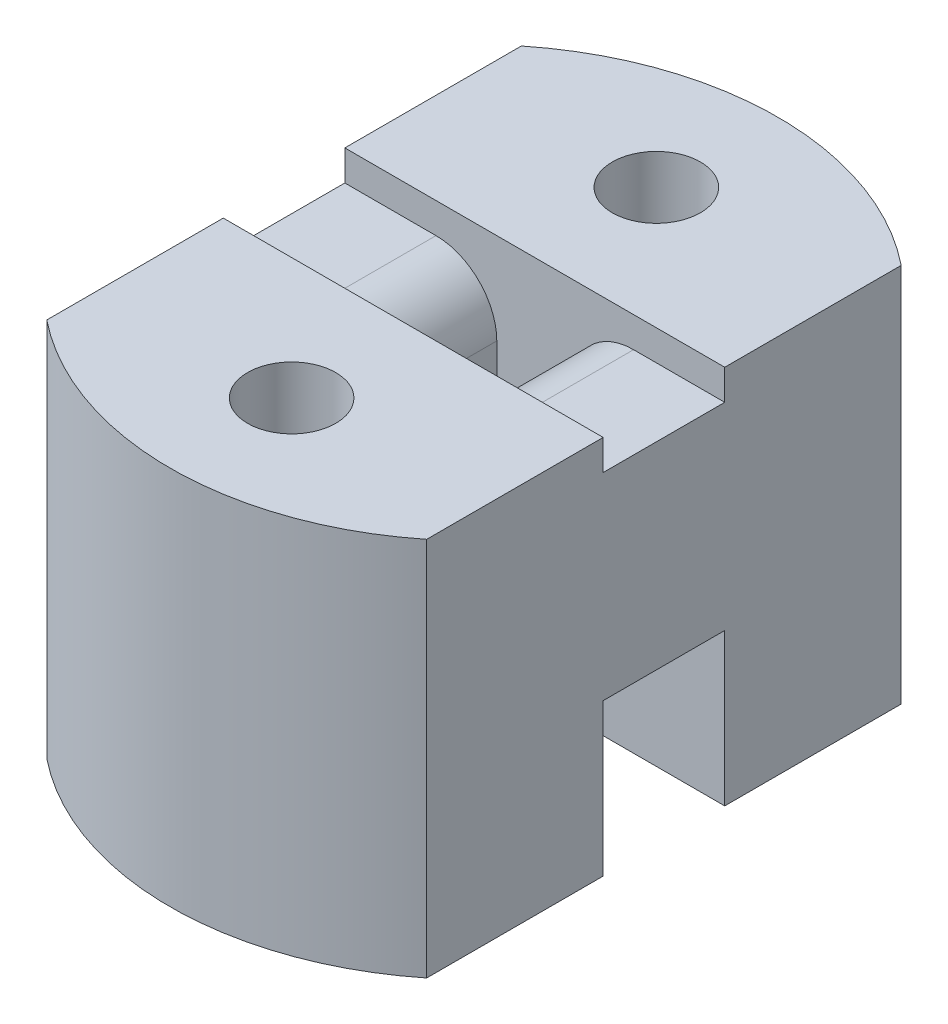
SolidWorks part; units mm, degrees
ref_plane "Front Plane" through (0, 0, 0) normal (0, 0, 1) x (1, 0, 0)
ref_plane "Top Plane" through (0, 0, 0) normal (0, 1, 0) x (1, 0, 0)
ref_plane "Right Plane" through (0, 0, 0) normal (1, 0, 0) x (0, 0, -1)
sketch "Sketch1" plane through (0, 0, 0) normal (0, 1, 0) x (1, 0, 0)
  circle A0 centre (0, 0) radius 20
  dimension "D1" = 40
extrude "Boss-Extrude1" add sketch "Sketch1" along normal blind 25
sketch "Sketch2" plane through (0, 25, 0) normal (0, 1, 0) x (1, 0, 0)
  line L0 (20, 0) -> (0, 0) construction
  line L1 (-20, 4) -> (20, 4)
  line L2 (-20, 4) -> (-20, -4)
  line L3 (-20, -4) -> (20, -4)
  line L4 (20, 4) -> (20, -4)
  circle A0 centre (0, 0) radius 20 construction
  dimension "D1" = 8
extrude "Cut-Extrude1" cut sketch "Sketch2" against normal blind 2
sketch "Sketch3" plane through (0, 25, 0) normal (0, 1, 0) x (1, 0, 0)
  line L0 (0, 0) -> (0, 12) construction
  line L3 (0, 0) -> (0, -12) construction
  dimension "D1" = 12
hole_wizard "M5 Clearance Hole1" positions "3DSketch1" profile "Sketch4" hole size "M5" standard "ANSI Metric" end condition through all
sketch3d "3DSketch1"
  point P0 (0, 25, -12)
  point P3 (0, 25, 12)
sketch "Sketch4" plane through (0, 25, -12) normal (1, 0, 0) x (0, 0, 1)
  line L0 (0, 0) -> (0, 25)
  line L1 (0, 25) -> (2.9, 25)
  line L2 (2.9, 25) -> (2.9, 0)
  line L5 (2.9, 0) -> (0, 0)
  line L11 (0, -6.35) -> (0, 107.95) construction
  dimension "Thru Hole Dia." = 5.8
  dimension "Thru Hole Depth" = 25
sketch "Sketch5" plane through (0, 0, 0) normal (0, -1, 0) x (1, 0, 0)
  line L1 (4.9075, 12) -> (2.4537, 16.25)
  line L2 (2.4537, 16.25) -> (-2.4537, 16.25)
  line L3 (-2.4537, 16.25) -> (-4.9075, 12)
  line L4 (-4.9075, 12) -> (-2.4537, 7.75)
  line L5 (-2.4537, 7.75) -> (2.4537, 7.75)
  line L6 (2.4537, 7.75) -> (4.9075, 12)
  line L7 (4.9075, -12) -> (2.4537, -7.75)
  line L8 (2.4537, -7.75) -> (-2.4537, -7.75)
  line L9 (-2.4537, -7.75) -> (-4.9075, -12)
  line L10 (-4.9075, -12) -> (-2.4537, -16.25)
  line L11 (-2.4537, -16.25) -> (2.4537, -16.25)
  line L12 (2.4537, -16.25) -> (4.9075, -12)
  circle A0 centre (0, 12) radius 4.25 construction
  circle A1 centre (0, -12) radius 4.25 construction
  dimension "D1" = 8.5
extrude "Cut-Extrude2" cut sketch "Sketch5" against normal blind 6 contours L5 L6 L1 L2 L3 L4
sketch "Sketch6" plane through (0, 23, 0) normal (0, 1, 0) x (1, 0, 0)
  line L0 (19.5959, 4) -> (-19.5959, 4) construction
  line L1 (-2.5, 4) -> (2.5, 4)
  line L2 (-2.5, 4) -> (-2.5, -4)
  line L3 (-2.5, -4) -> (2.5, -4)
  line L4 (2.5, 4) -> (2.5, -4)
  line L5 (-19.5959, -4) -> (19.5959, -4) construction
  point P8 (0, 4)
  dimension "D1" = 5
extrude "Cut-Extrude3" cut sketch "Sketch6" against normal through all both and the other way through all
sketch "Sketch7" plane through (0, 0, 0) normal (0, -1, 0) x (1, 0, 0)
  line L0 (-20, -4) -> (-20, 4) construction
  line L1 (20, -4) -> (20, 4) construction
  line L2 (-20, -4) -> (20, -4) construction
  line L3 (-20, 4) -> (20, 4) construction
  line L4 (-20, -4) -> (-20, 4)
  line L5 (20, -4) -> (20, 4)
  line L6 (-20, -4) -> (20, -4)
  line L7 (-20, 4) -> (20, 4)
extrude "Cut-Extrude4" cut sketch "Sketch7" against normal blind 10
fillet "Fillet1" radius 4 4 edges at (-2.5, 23, 0) (2.5, 23, 0) (-2.5, 10, 0) (2.5, 10, 0)
sketch "Sketch8" plane through (0, 25, 0) normal (0, 1, 0) x (1, 0, 0)
  line L0 (0, 0) -> (0, 20) construction
  line L1 (-12.5, 20) -> (12.5, 20)
  line L2 (-12.5, 20) -> (-12.5, -20)
  line L3 (-12.5, -20) -> (12.5, -20)
  line L4 (12.5, 20) -> (12.5, -20)
  arc A0 (19.5959, 4) -> (-19.5959, 4) centre (0, 0) ccw construction
  arc A1 (-19.5959, -4) -> (19.5959, -4) centre (0, 0) ccw construction
  point P7 (0, 0)
  dimension "D1" = 25
extrude "Cut-Extrude5" cut sketch "Sketch8" against normal through all flip side to cut
